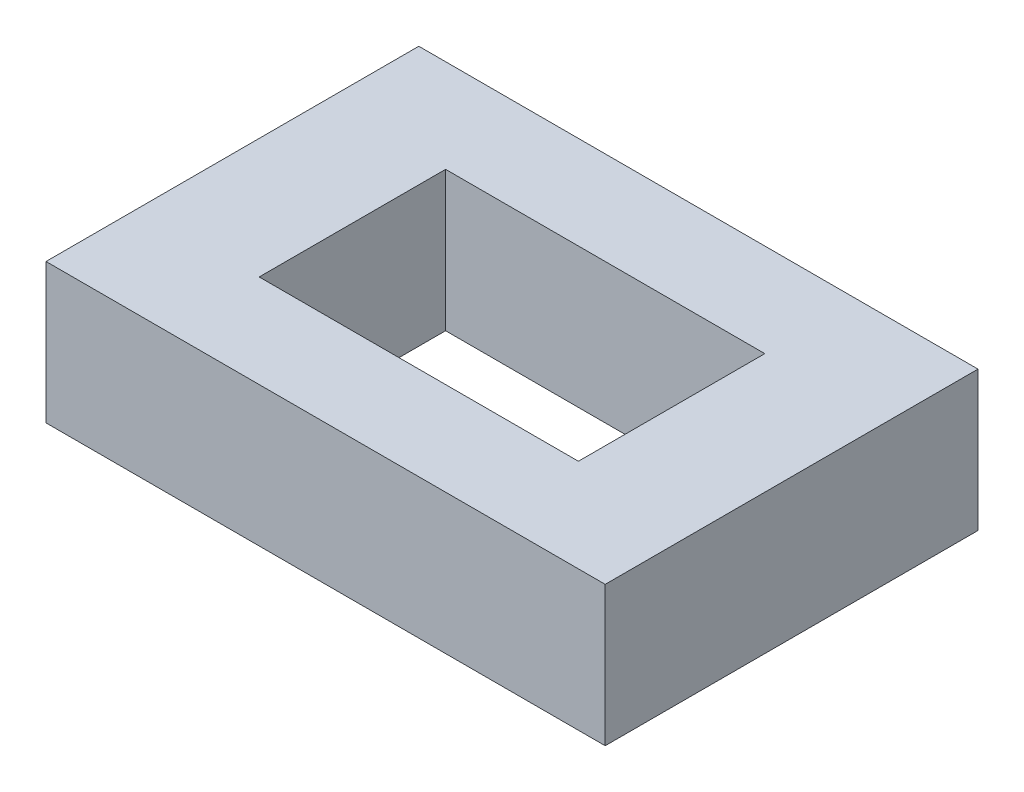
SolidWorks part; units mm, degrees
ref_plane "Front Plane" through (0, 0, 0) normal (0, 0, 1) x (1, 0, 0)
ref_plane "Top Plane" through (0, 0, 0) normal (0, 1, 0) x (1, 0, 0)
ref_plane "Right Plane" through (0, 0, 0) normal (1, 0, 0) x (0, 0, -1)
sketch "Sketch1" plane through (0, 0, 0) normal (0, 1, 0) x (1, 0, 0)
  line L1 (-6, -4) -> (6, -4)
  line L2 (-6, -4) -> (-6, 4)
  line L3 (-6, 4) -> (6, 4)
  line L4 (6, -4) -> (6, 4)
  line L5 (-6, -4) -> (6, 4) construction
  line L6 (-6, 4) -> (6, -4) construction
  point P0 (0, 0)
  dimension "D1" = 12
  dimension "D2" = 8
extrude "Boss-Extrude1" add sketch "Sketch1" along normal blind 3
sketch "Sketch2" plane through (0, 3, 0) normal (0, 1, 0) x (1, 0, 0)
  line L1 (-3.425, -2) -> (3.425, -2)
  line L2 (-3.425, -2) -> (-3.425, 2)
  line L3 (-3.425, 2) -> (3.425, 2)
  line L4 (3.425, -2) -> (3.425, 2)
  line L5 (-3.425, -2) -> (3.425, 2) construction
  line L6 (-3.425, 2) -> (3.425, -2) construction
  point P0 (0, 0)
  dimension "D1" = 6.85
  dimension "D2" = 4
extrude "Cut-Extrude1" cut sketch "Sketch2" against normal blind 3
